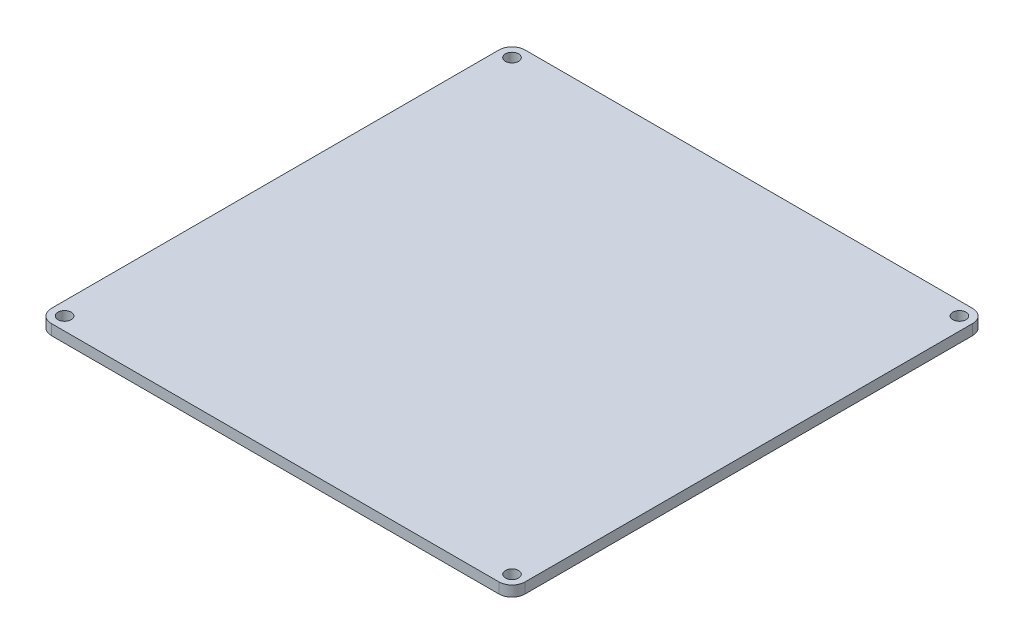
SolidWorks part; units mm, degrees
ref_plane "Alzado" through (0, 0, 0) normal (0, 0, 1) x (1, 0, 0)
ref_plane "Planta" through (0, 0, 0) normal (0, 1, 0) x (1, 0, 0)
ref_plane "Vista lateral" through (0, 0, 0) normal (1, 0, 0) x (0, 0, -1)
sketch "Croquis1" plane through (0, 0, 0) normal (0, 1, 0) x (1, 0, 0)
  line L0 (0, 0) -> (180, 180) construction
  line L1 (0, 0) -> (180, 0)
  line L2 (0, 0) -> (0, 180)
  line L3 (0, 180) -> (180, 180)
  line L4 (180, 0) -> (180, 180)
  line L5 (5, 5) -> (175, 5) construction
  line L6 (5, 5) -> (5, 175) construction
  line L7 (5, 175) -> (175, 175) construction
  line L8 (175, 5) -> (175, 175) construction
  line L9 (5, 175) -> (175, 5) construction
  circle A0 centre (5, 175) radius 2.5
  circle A1 centre (175, 175) radius 2.5
  circle A2 centre (175, 5) radius 2.5
  circle A3 centre (5, 5) radius 2.5
  point P9 (90, 90)
  point P10 (90, 90)
  dimension "D3" = 5
  dimension "D1" = 180
  dimension "D2" = 170
extrude "Saliente-Extruir1" add sketch "Croquis1" along normal blind 4
fillet "Redondeo1" radius 5 4 edges at (0, 2, -180) (180, 2, -180) (180, 2, 0) (0, 2, 0)
